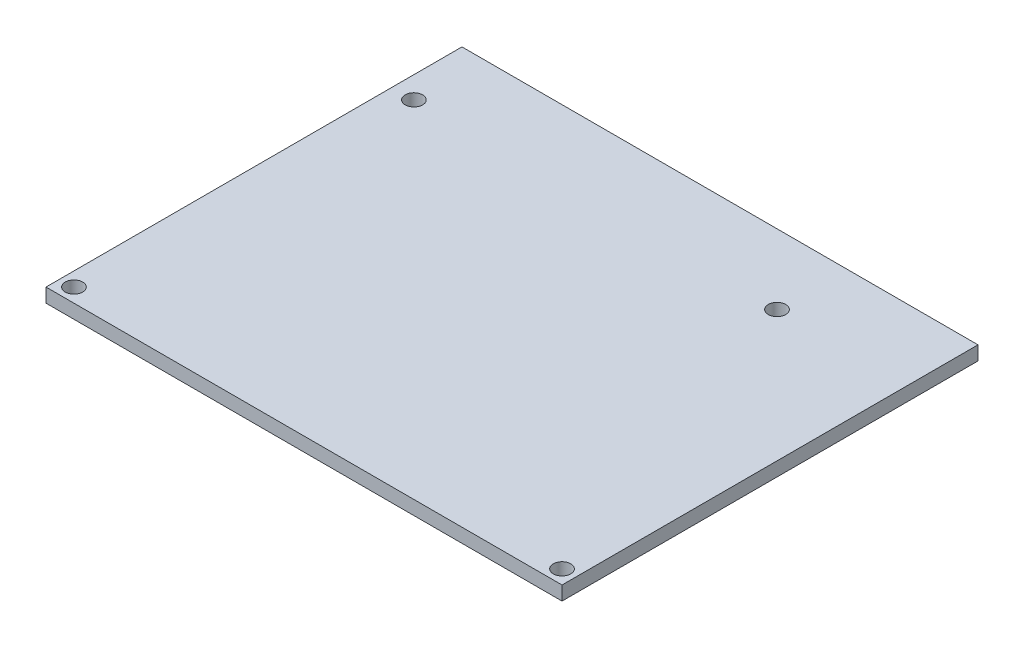
SolidWorks part; units mm, degrees
ref_plane "Front Plane" through (0, 0, 0) normal (0, 0, 1) x (1, 0, 0)
ref_plane "Top Plane" through (0, 0, 0) normal (0, 1, 0) x (1, 0, 0)
ref_plane "Right Plane" through (0, 0, 0) normal (1, 0, 0) x (0, 0, -1)
sketch "Sketch1" plane through (0, 0, 0) normal (0, 1, 0) x (1, 0, 0)
  line L1 (0, 0) -> (59.05, 0)
  line L2 (0, 0) -> (0, 47.6)
  line L3 (0, 47.6) -> (59.05, 47.6)
  line L4 (59.05, 0) -> (59.05, 47.6)
  circle A0 centre (57.45, 1.6) radius 1
  circle A1 centre (44.05, 39.6) radius 1
  circle A2 centre (2.5, 39.6) radius 1
  circle A3 centre (1.6, 1.6) radius 1
  dimension "D3" = 2
  dimension "D1" = 47.6
  dimension "D2" = 59.05
  dimension "D4" = 1.6
  dimension "D5" = 1.6
  dimension "D6" = 15
  dimension "D7" = 8
  dimension "D8" = 8
  dimension "D10" = 1.6
  dimension "D11" = 1.6
  dimension "D9" = 2.5
extrude "Boss-Extrude1" add sketch "Sketch1" along normal blind 1.6
equation "\"D5@Sketch1\"=\"D4@Sketch1\""
equation "\"D8@Sketch1\"=\"D7@Sketch1\""
